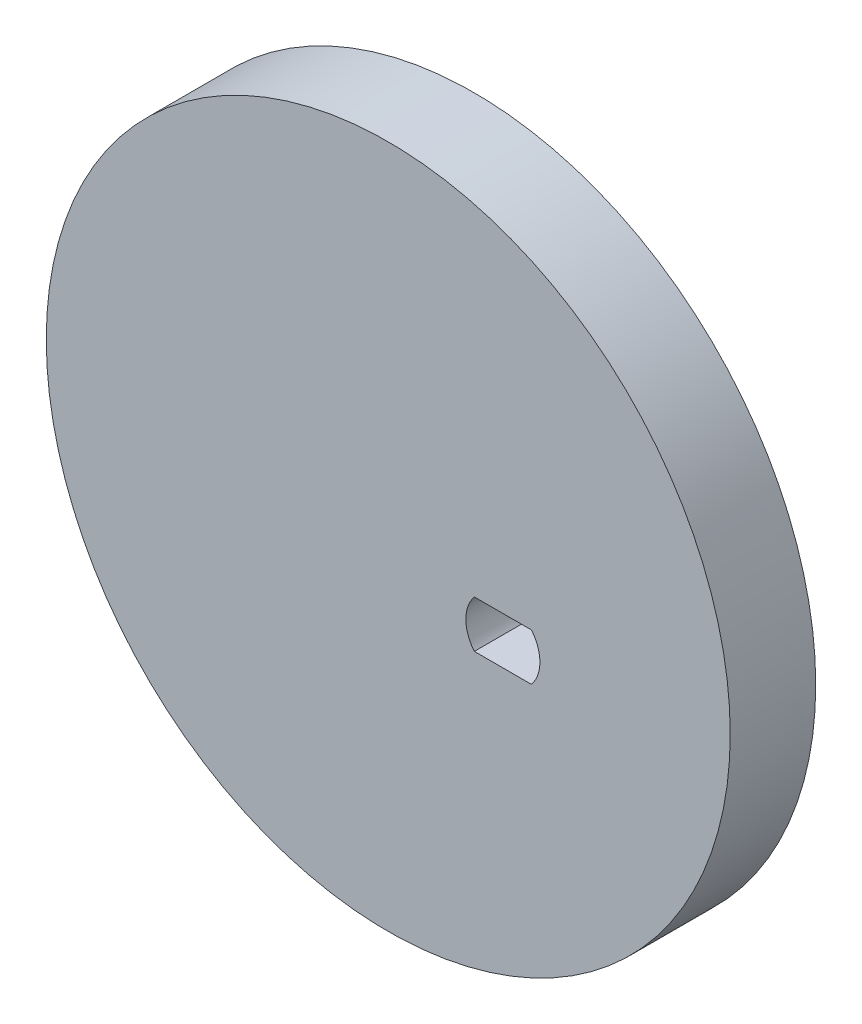
SolidWorks part; units mm, degrees
ref_plane "Front Plane" through (0, 0, 0) normal (0, 0, 1) x (1, 0, 0)
ref_plane "Top Plane" through (0, 0, 0) normal (0, 1, 0) x (1, 0, 0)
ref_plane "Right Plane" through (0, 0, 0) normal (1, 0, 0) x (0, 0, -1)
sketch "Sketch1" plane through (0, 0, 0) normal (0, 0, 1) x (1, 0, 0)
  line L4 (-2.1213, 1.75) -> (2.1213, 1.75)
  line L5 (-2.1213, -1.75) -> (2.1213, -1.75)
  arc A10 (-2.1213, 1.75) -> (-2.1213, -1.75) centre (0, 0) ccw
  arc A11 (2.1213, 1.75) -> (2.1213, -1.75) centre (0, 0) cw
  circle A15 centre (-8.5147, 2.4305) radius 25.4
  point P2 (0, 0)
  point P3 (0, 0)
  dimension "D1" = 4.2426
  dimension "D2" = 4.2426
  dimension "D3" = 2.75
  dimension "D4" = 2.75
  dimension "2" = 50.8
extrude "Boss-Extrude1" add sketch "Sketch1" along normal blind 6.35
